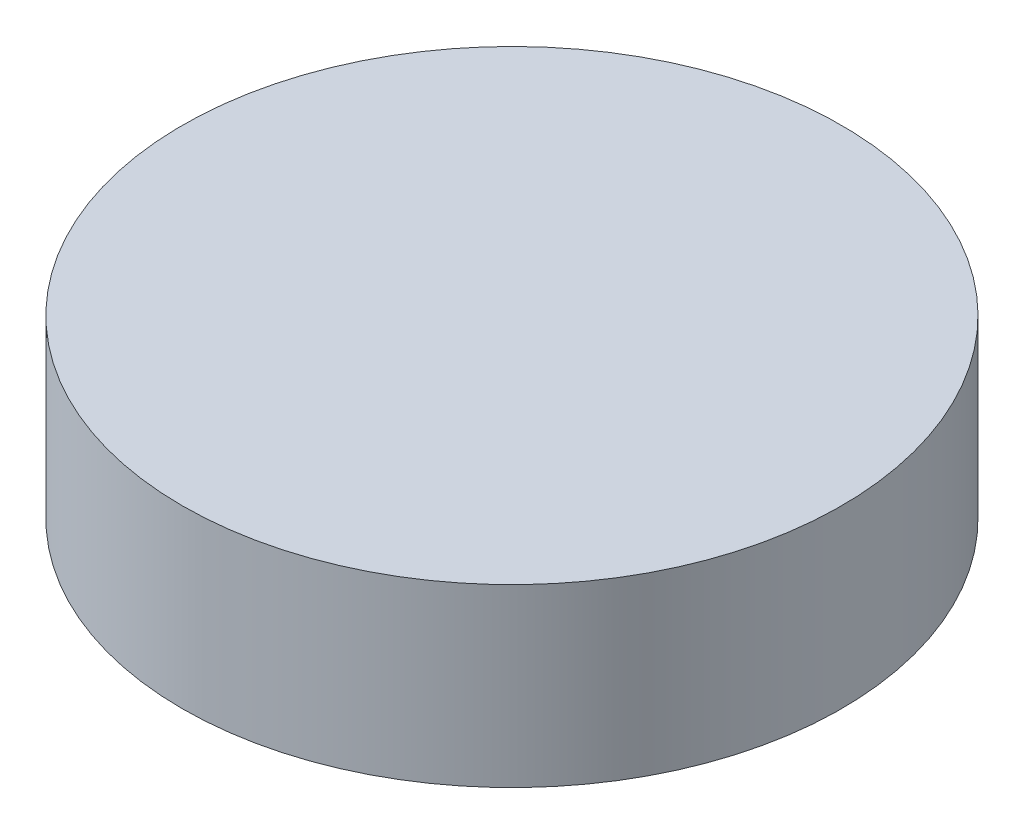
SolidWorks part; units mm, degrees
ref_plane "Front Plane" through (0, 0, 0) normal (0, 0, 1) x (1, 0, 0)
ref_plane "Top Plane" through (0, 0, 0) normal (0, 1, 0) x (1, 0, 0)
ref_plane "Right Plane" through (0, 0, 0) normal (1, 0, 0) x (0, 0, -1)
sketch "Sketch1" plane through (0, 0, 0) normal (0, 1, 0) x (1, 0, 0)
  circle A0 centre (0, 0) radius 9.525
  dimension "D1" = 19.05
extrude "Boss-Extrude1" add sketch "Sketch1" along normal blind 5.08
sketch "Sketch2" plane through (0, 0, 0) normal (0, -1, 0) x (1, 0, 0)
  circle A0 centre (0, 0) radius 2.8702
  dimension "D1" = 5.7404
extrude "Cut-Extrude1" cut sketch "Sketch2" against normal blind 2.54
